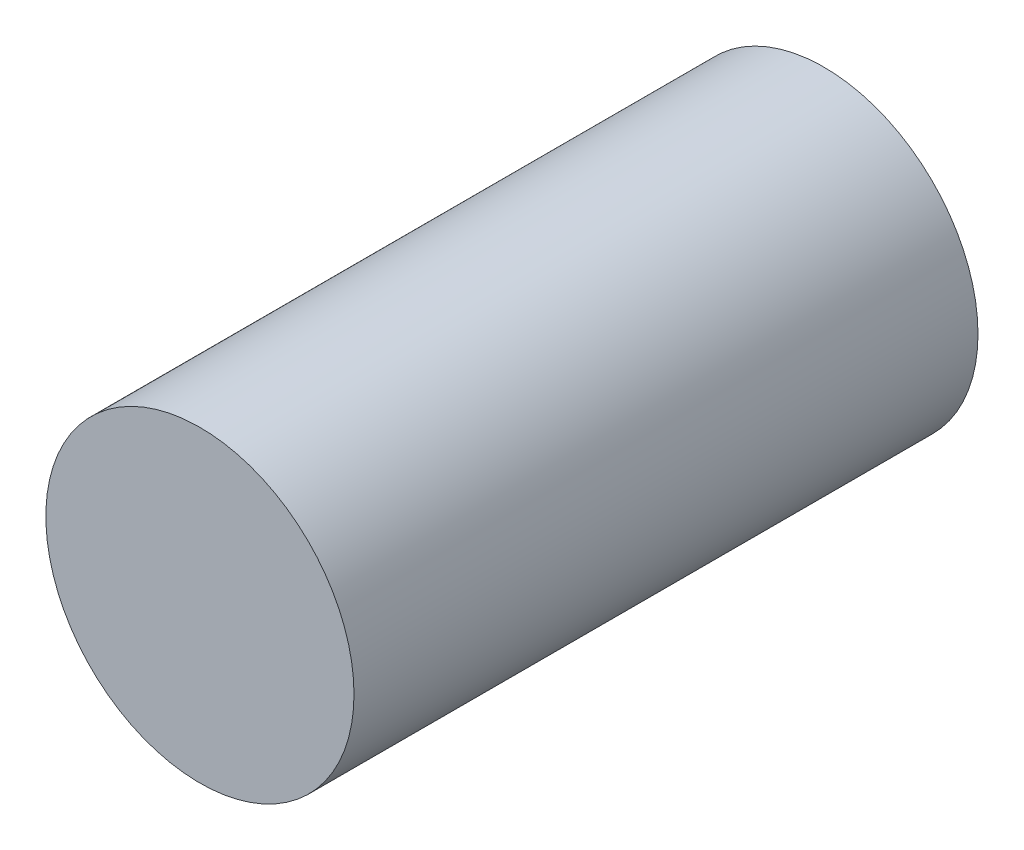
SolidWorks part; units mm, degrees
ref_plane "Front Plane" through (0, 0, 0) normal (0, 0, 1) x (1, 0, 0)
ref_plane "Top Plane" through (0, 0, 0) normal (0, 1, 0) x (1, 0, 0)
ref_plane "Right Plane" through (0, 0, 0) normal (1, 0, 0) x (0, 0, -1)
sketch "Sketch1" plane through (0, 0, 0) normal (0, 0, 1) x (1, 0, 0)
  circle A0 centre (0, 0) radius 40
  dimension "D1" = 80
extrude "Boss-Extrude1" add sketch "Sketch1" along normal blind 162
